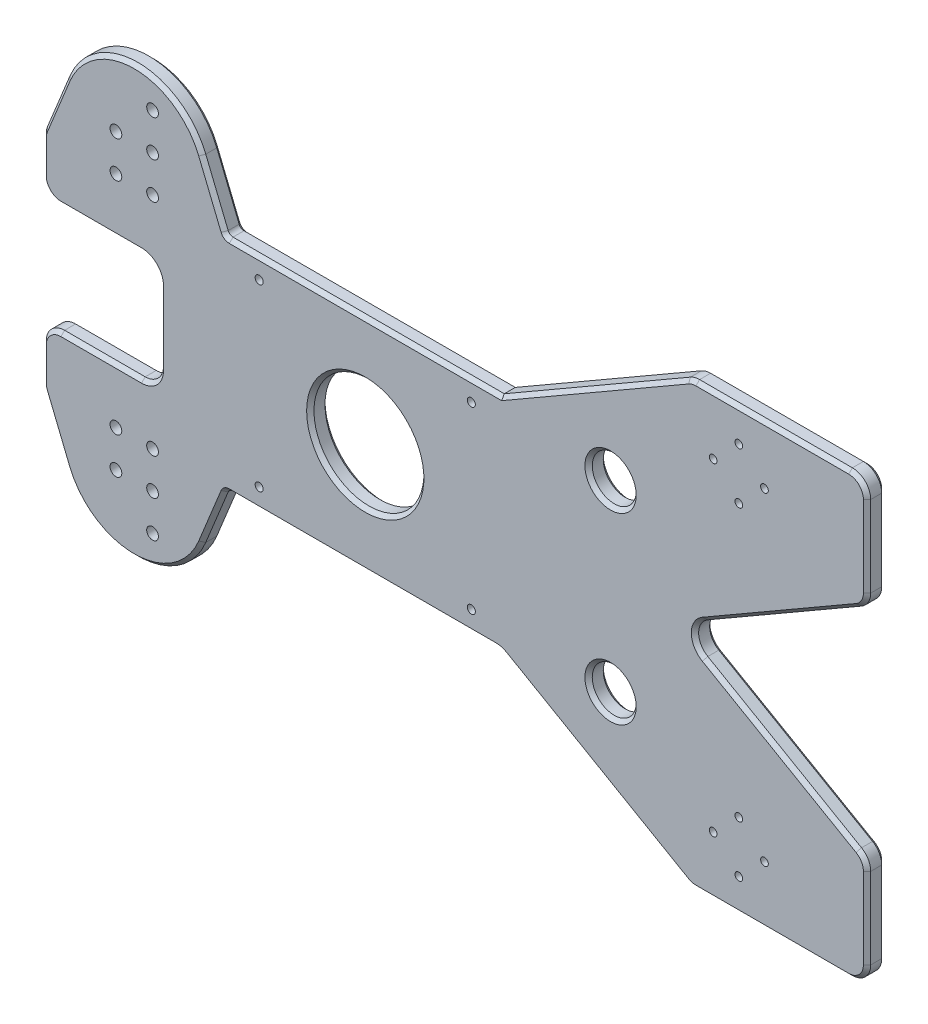
SolidWorks part; units mm, degrees
ref_plane "前视基准面" through (0, 0, 0) normal (0, 0, 1) x (1, 0, 0)
ref_plane "上视基准面" through (0, 0, 0) normal (0, 1, 0) x (1, 0, 0)
ref_plane "右视基准面" through (0, 0, 0) normal (1, 0, 0) x (0, 0, -1)
other "Configuration Table"
sketch "草图1" plane through (0, 0, 0) normal (0, 0, 1) x (1, 0, 0)
  line L0 (-125, 29) -> (-125, 20)
  line L5 (95, -60) -> (53.3013, -60)
  line L6 (100, -55) -> (100, -32.8868)
  line L16 (95, 60) -> (53.3013, 60)
  line L18 (-99.9959, -38.3386) -> (-99.9959, 38.3386) construction
  line L20 (-120, 15) -> (-98, 15)
  line L21 (-93, 10) -> (-93, -10)
  line L22 (-98, -15) -> (-120, -15)
  line L23 (-125, -20) -> (-125, -29)
  line L24 (0, 0) -> (-305.8506, 0) construction
  line L26 (1.1603, -30.6699) -> (50.8013, -59.3301)
  line L27 (0, 0) -> (0, 30) construction
  line L29 (0, 30) -> (50.8013, 59.3301)
  line L32 (0, 60) -> (0, 113.2979) construction
  line L34 (-74.042, 30) -> (0, 30)
  line L36 (-74.042, -30) -> (-1.3397, -30)
  line L37 (97.5, 28.5566) -> (55.5385, 4.3301)
  line L38 (55.5385, -4.3301) -> (97.5, -28.5566)
  line L39 (100, 32.8868) -> (100, 55)
  line L42 (-81.4751, 45.8871) -> (-75.3616, 30.8871)
  line L43 (-75.3616, -30.8871) -> (-81.4751, -45.8871)
  line L44 (-118.5167, 45.8871) -> (-124.6302, 30.8871)
  line L45 (-118.5167, -45.8871) -> (-124.6302, -30.8871)
  line L46 (-103.6459, -15) -> (-103.6459, 15) construction
  arc A14 (50.8013, 59.3301) -> (53.3013, 60) centre (53.3013, 55) cw
  arc A15 (100, 55) -> (95, 60) centre (95, 55) ccw
  arc A16 (95, -60) -> (100, -55) centre (95, -55) ccw
  arc A17 (50.8013, -59.3301) -> (53.3013, -60) centre (53.3013, -55) ccw
  arc A20 (-93, -10) -> (-98, -15) centre (-98, -10) cw
  arc A21 (-98, 15) -> (-93, 10) centre (-98, 10) cw
  arc A22 (-125, 20) -> (-120, 15) centre (-120, 20) ccw
  arc A23 (-120, -15) -> (-125, -20) centre (-120, -20) ccw
  arc A26 (97.5, -28.5566) -> (100, -32.8868) centre (95, -32.8868) cw
  arc A27 (97.5, 28.5566) -> (100, 32.8868) centre (95, 32.8868) ccw
  arc A28 (55.5385, 4.3301) -> (55.5385, -4.3301) centre (58.0385, 0) ccw
  arc A29 (-1.3397, -30) -> (1.1603, -30.6699) centre (-1.3397, -35) cw
  arc A35 (-74.042, 30) -> (-75.3616, 30.8871) centre (-74.042, 31.4249) cw
  arc A36 (-74.042, -30) -> (-75.3616, -30.8871) centre (-74.042, -31.4249) ccw
  arc A38 (-125, 29) -> (-124.6302, 30.8871) centre (-120, 29) cw
  arc A39 (-125, -29) -> (-124.6302, -30.8871) centre (-120, -29) ccw
  arc A40 (-118.5167, -45.8871) -> (-81.4751, -45.8871) centre (-99.9959, -38.3386) ccw
  arc A41 (-118.5167, 45.8871) -> (-81.4751, 45.8871) centre (-99.9959, 38.3386) cw
  point P0 (0, 0)
  point P18 (-125, 24.5)
  point P28 (51.9615, 60)
  point P37 (51.9615, -60)
  point P40 (0, -30)
  point P42 (0, 0)
  point P43 (0, 0)
  point P46 (-93, -15)
  point P49 (-93, 15)
  point P53 (-125, 15)
  point P56 (0, 0)
  point P64 (100, -30)
  point P67 (100, 30)
  point P70 (48.0385, 0)
  point P73 (0, -30)
  point P89 (-75, 30)
  dimension "D9" = 60
  dimension "D6" = 75
  dimension "D10" = 5
  dimension "D11" = 5
  dimension "D7" = 5
  dimension "D13" = 20
  dimension "D14" = 5
  dimension "D2" = 30
  dimension "D3" = 120
  dimension "D4" = 32
  dimension "D5" = 30
  dimension "D8" = 15
  dimension "D12" = 60
  dimension "D15" = 15
  dimension "D16" = 125
  dimension "D17" = 30
  dimension "D18" = 100
  dimension "D19" = 9
extrude "凸台-拉伸1" add sketch "草图1" along normal mid plane 5
sketch "草图2" plane through (0, 0, 2.5) normal (0, 0, 1) x (1, 0, 0)
  line L0 (0, 0) -> (-173.1109, 0) construction
  line L1 (-94.9959, 40) -> (-104.9959, 40) construction
  line L3 (-94.9959, -40) -> (-104.9959, -40) construction
  line L4 (-104.9959, 30) -> (-94.9959, 30) construction
  line L5 (-104.9959, -30) -> (-94.9959, -30) construction
  line L6 (-94.9959, 40) -> (-94.9959, 30) construction
  line L7 (-104.9959, 40) -> (-104.9959, 30) construction
  line L8 (-99.9959, -38.3386) -> (-99.9959, 60) construction
  line L12 (-94.9959, 50) -> (-94.9959, 40) construction
  circle A0 centre (-104.9959, 40) radius 1.6
  circle A1 centre (-94.9959, 40) radius 1.6
  circle A2 centre (-94.9959, -40) radius 1.6
  circle A3 centre (-104.9959, -40) radius 1.6
  circle A4 centre (-104.9959, 30) radius 1.6
  circle A5 centre (-94.9959, 30) radius 1.6
  circle A6 centre (-94.9959, -30) radius 1.6
  circle A7 centre (-104.9959, -30) radius 1.6
  arc A8 (-118.5167, -45.8871) -> (-81.4751, -45.8871) centre (-99.9959, -38.3386) ccw construction
  circle A9 centre (-94.9959, 50) radius 1.6
  circle A10 centre (-94.9959, -50) radius 1.6
  dimension "D1" = 3.2
  dimension "D2" = 3.2
  dimension "D6" = 10
  dimension "D3" = 3.2
  dimension "D4" = 40
  dimension "D5" = 10
  dimension "D7" = 10
extrude "切除-拉伸1" cut sketch "草图2" against normal through all
sketch "草图3" plane through (0, 0, 2.5) normal (0, 0, 1) x (1, 0, 0)
  line L0 (0, 0) -> (165.1711, 0) construction
  line L3 (100, -55) -> (100, -32.8868) construction
  circle A0 centre (65, 44.1) radius 7 construction
  circle A1 centre (65, 51.1) radius 1.05
  circle A2 centre (72, 44.1) radius 1.05
  circle A3 centre (58, 44.1) radius 1.05
  circle A4 centre (65, 37.1) radius 1.05
  circle A5 centre (65, -44.1) radius 7 construction
  circle A6 centre (65, -37.1) radius 1.05
  circle A7 centre (58, -44.1) radius 1.05
  circle A8 centre (72, -44.1) radius 1.05
  circle A9 centre (65, -51.1) radius 1.05
  dimension "D1" = 14
  dimension "D2" = 35
  dimension "D3" = 88.2
  dimension "D4" = 2.1
extrude "切除-拉伸2" cut sketch "草图3" against normal through all
sketch "草图4" plane through (0, 0, 2.5) normal (0, 0, 1) x (1, 0, 0)
  line L0 (0, 0) -> (-180.6786, 0) construction
  line L2 (-65.894, -24.476) -> (-8, -24.476) construction
  line L3 (-65.894, -24.476) -> (-65.894, 24.476) construction
  line L4 (-65.894, 24.476) -> (-8, 24.476) construction
  line L5 (-8, -24.476) -> (-8, 24.476) construction
  line L6 (-65.894, -24.476) -> (-8, 24.476) construction
  line L7 (-65.894, 24.476) -> (-8, -24.476) construction
  circle A0 centre (-65.894, 24.476) radius 1.1
  circle A1 centre (-65.894, -24.476) radius 1.1
  circle A2 centre (-8, -24.476) radius 1.1
  circle A3 centre (-8, 24.476) radius 1.1
  circle A4 centre (-36.947, 0) radius 15
  circle A5 centre (30, 25) radius 6
  circle A6 centre (30, -25) radius 6
  point P3 (-36.947, 0)
  dimension "D4" = 2.2
  dimension "D5" = 30
  dimension "D6" = 50
  dimension "D7" = 12
  dimension "D1" = 57.894
  dimension "D2" = 48.952
  dimension "D3" = 8
  dimension "D8" = 30
extrude "切除-拉伸3" cut sketch "草图4" against normal through all
chamfer "倒角1" distance 1 angle 45 74 edges at (25.4006, 44.6651, -2.5) (52.0072, 59.8296, -2.5) (74.1506, 60, -2.5) (98.5355, 58.5355, -2.5) (-37.021, 30, -2.5) (100, 43.9434, -2.5) (-74.837, 30.2424, -2.5) (99.3301, 30.3868, -2.5) (-78.4183, 38.3871, -2.5) (76.5192, 16.4434, -2.5) (53.0385, 0, -2.5) (76.5192, -16.4434, -2.5) (99.3301, -30.3868, -2.5) (-125, 24.5, -2.5) (100, -43.9434, -2.5) (-123.5355, 16.4645, -2.5) (98.5355, -58.5355, -2.5) (-109, 15, -2.5) (74.1506, -60, -2.5) (-94.4645, 13.5355, -2.5) (52.0072, -59.8296, -2.5) (-93, 0, -2.5) (25.9808, -45, -2.5) (-94.4645, -13.5355, -2.5) (-0.0457, -30.1704, -2.5) (-109, -15, -2.5) (-37.6909, -30, -2.5) (-123.5355, -16.4645, -2.5) (-74.837, -30.2424, -2.5) (-125, -24.5, -2.5) (-78.4183, -38.3871, -2.5) (25.4006, 44.6651, 2.5) (52.0072, 59.8296, 2.5) (74.1506, 60, 2.5) (98.5355, 58.5355, 2.5) (100, 43.9434, 2.5) (99.3301, 30.3868, 2.5) (76.5192, 16.4434, 2.5) (53.0385, 0, 2.5) (76.5192, -16.4434, 2.5) (99.3301, -30.3868, 2.5) (100, -43.9434, 2.5) (98.5355, -58.5355, 2.5) (74.1506, -60, 2.5) (52.0072, -59.8296, 2.5) (25.9808, -45, 2.5) (-0.0457, -30.1704, 2.5) (-37.6909, -30, 2.5) (-74.837, -30.2424, 2.5) (-78.4183, -38.3871, 2.5) (-125, -24.5, 2.5) (-123.5355, -16.4645, 2.5) (-37.021, 30, 2.5) (-109, -15, 2.5) (-74.837, 30.2424, 2.5) (-94.4645, -13.5355, 2.5) (-78.4183, 38.3871, 2.5) (-93, 0, 2.5) (-94.4645, 13.5355, 2.5) (-109, 15, 2.5) (-123.5355, 16.4645, 2.5) (-125, 24.5, 2.5) (-121.5734, 38.3871, -2.5) (-124.9067, 29.9615, -2.5) (-124.9067, -29.9615, -2.5) (-121.5734, -38.3871, -2.5) (-121.5734, -38.3871, 2.5) (-124.9067, -29.9615, 2.5) (-121.5734, 38.3871, 2.5) (-124.9067, 29.9615, 2.5) (-99.9959, -58.3386, 2.5) (-99.9959, 58.3386, 2.5) (-99.9959, 58.3386, -2.5) (-99.9959, -58.3386, -2.5)
chamfer "倒角2" distance 1 angle 45 6 edges at (-21.947, 0, 2.5) (-21.947, 0, -2.5) (36, 25, -2.5) (36, -25, -2.5) (36, -25, 2.5) (36, 25, 2.5)
